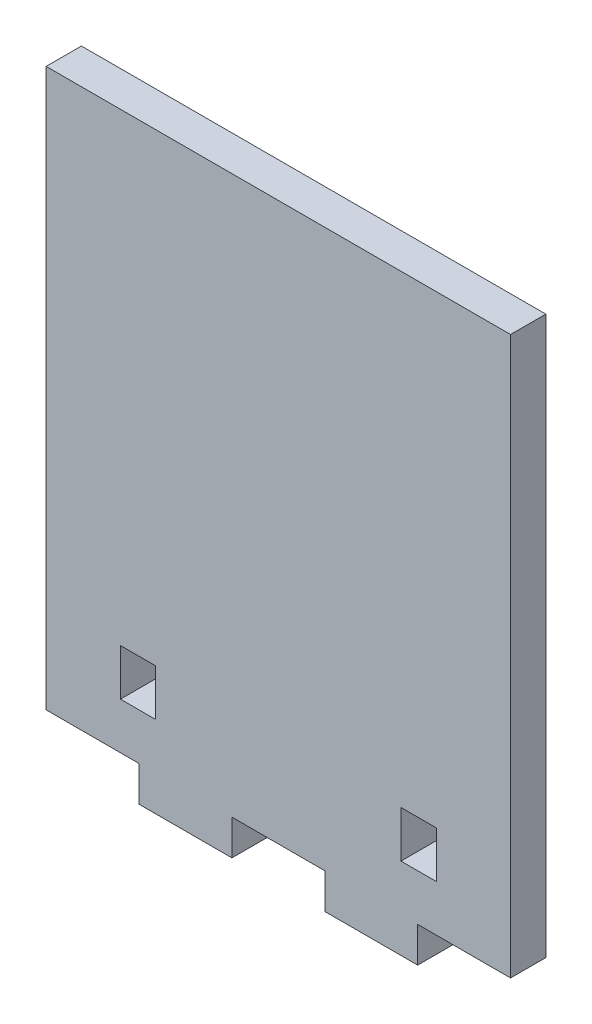
SolidWorks part; units mm, degrees
ref_plane "Front Plane" through (0, 0, 0) normal (0, 0, 1) x (1, 0, 0)
ref_plane "Top Plane" through (0, 0, 0) normal (0, 1, 0) x (1, 0, 0)
ref_plane "Right Plane" through (0, 0, 0) normal (1, 0, 0) x (0, 0, -1)
sketch "Sketch1" plane through (0, 0, 0) normal (0, 0, 1) x (1, 0, 0)
  line L1 (0, 0) -> (63.5, 0)
  line L2 (0, 0) -> (0, 81.026)
  line L3 (0, 81.026) -> (63.5, 81.026)
  line L4 (63.5, 0) -> (63.5, 81.026)
  dimension "D1" = 81.026
  dimension "D2" = 63.5
extrude "Boss-Extrude1" add sketch "Sketch1" along normal blind 4.826
sketch "Sketch2" plane through (0, 0, 4.826) normal (0, 0, 1) x (1, 0, 0)
  line L0 (0, 0) -> (63.5, 0) construction
  line L1 (0, 0) -> (12.7, 0)
  line L2 (0, 0) -> (0, 4.826)
  line L3 (0, 4.826) -> (12.7, 4.826)
  line L4 (12.7, 0) -> (12.7, 4.826)
  line L5 (25.4, 0) -> (38.1, 0)
  line L6 (25.4, 0) -> (25.4, 4.826)
  line L7 (25.4, 4.826) -> (38.1, 4.826)
  line L8 (38.1, 0) -> (38.1, 4.826)
  line L9 (12.7, 4.826) -> (25.4, 4.826) construction
  line L10 (63.5, 0) -> (50.8, 0)
  line L11 (63.5, 0) -> (63.5, 4.826)
  line L12 (63.5, 4.826) -> (50.8, 4.826)
  line L13 (50.8, 0) -> (50.8, 4.826)
  line L14 (38.1, 4.826) -> (50.8, 4.826) construction
  dimension "D1" = 4.826
extrude "Cut-Extrude1" cut sketch "Sketch2" against normal through all
sketch "Sketch3" plane through (0, 0, 0) normal (0, 0, -1) x (-1, 0, 0)
  line L0 (-53.34, 17.526) -> (-53.34, 11.176) construction
  line L1 (-53.34, 17.526) -> (-48.514, 17.526) construction
  line L2 (-48.514, 17.526) -> (-48.514, 11.176) construction
  line L3 (-53.34, 11.176) -> (-48.514, 11.176) construction
  line L4 (-14.986, 17.526) -> (-14.986, 11.176) construction
  line L5 (-14.986, 17.526) -> (-10.16, 17.526) construction
  line L6 (-10.16, 17.526) -> (-10.16, 11.176) construction
  line L7 (-14.986, 11.176) -> (-10.16, 11.176) construction
  line L8 (-53.34, 17.526) -> (-53.34, 11.176)
  line L9 (-53.34, 17.526) -> (-48.514, 17.526)
  line L10 (-48.514, 17.526) -> (-48.514, 11.176)
  line L11 (-53.34, 11.176) -> (-48.514, 11.176)
  line L12 (-50.8, 4.826) -> (-50.8, 0)
  line L13 (-50.8, 0) -> (-38.1, 0)
  line L14 (-38.1, 0) -> (-38.1, 4.826)
  line L15 (-38.1, 4.826) -> (-25.4, 4.826)
  line L16 (-25.4, 4.826) -> (-25.4, 0)
  line L17 (-25.4, 0) -> (-12.7, 0)
  line L18 (-12.7, 0) -> (-12.7, 4.826)
  line L19 (-12.7, 4.826) -> (0, 4.826)
  line L20 (0, 4.826) -> (0, 81.026)
  line L21 (0, 81.026) -> (-63.5, 81.026)
  line L22 (-63.5, 81.026) -> (-63.5, 4.826)
  line L23 (-63.5, 4.826) -> (-50.8, 4.826)
  line L24 (-50.8, 4.826) -> (-50.8, 0)
  line L25 (-50.8, 0) -> (-38.1, 0)
  line L26 (-38.1, 0) -> (-38.1, 4.826)
  line L27 (-38.1, 4.826) -> (-25.4, 4.826)
  line L28 (-25.4, 4.826) -> (-25.4, 0)
  line L29 (-25.4, 0) -> (-12.7, 0)
  line L30 (-12.7, 0) -> (-12.7, 4.826)
  line L31 (-12.7, 4.826) -> (0, 4.826)
  line L32 (0, 4.826) -> (0, 81.026)
  line L33 (0, 81.026) -> (-63.5, 81.026)
  line L34 (-63.5, 81.026) -> (-63.5, 4.826)
  line L35 (-63.5, 4.826) -> (-50.8, 4.826)
  line L36 (-14.986, 17.526) -> (-14.986, 11.176)
  line L37 (-14.986, 17.526) -> (-10.16, 17.526)
  line L38 (-10.16, 17.526) -> (-10.16, 11.176)
  line L39 (-14.986, 11.176) -> (-10.16, 11.176)
  dimension "D1" = 0
extrude "Cut-Extrude2" cut sketch "Sketch3" against normal blind 4.826 contours L8 L11 L10 L9 | L36 L39 L38 L37
equation "\"MDF\"= 0.19in"
equation "\"PVCID\" = 2.067in"
equation "\"PVCOD\" = 2.375in"
equation "\"GenDiameter\"= 60mm"
equation "\"GenCutDiameter\" = 1.8in"
equation "\"GenCutDistance\" = 1"
equation "\"TowerHeight\" = 6in"
equation "\"TowerFrontBase\" = 3in"
equation "\"FunnelHeight\" = 1in"
equation "\"FunnelAngle\" = 20"
equation "\"TowerSideBase\" = 3in"
equation "\"TowerPanelLength\" = 2in"
equation "\"TowerPanelLeeway\" = 0.5in"
equation "\"BaseLength\" = 9in"
equation "\"BaseWidth\" = 10in"
equation "\"WheelHoleLength\" = 3.25in"
equation "\"WheelHoleWidth\" = 26mm"
equation "\"WheelHoleFromBack\" = 1.5in"
equation "\"DropLength\" = 1in"
equation "\"DropWidth\" = 8.5in"
equation "\"BumperWidth\" = 2in"
equation "\"SmallHexDiameter\" = 0.185in"
equation "\"SmallHexHeight\" = 0.701in"
equation "\"ScrewSize\" = 0.106in"
equation "\"BigHexDiameter\" = 0.251in"
equation "\"BigHexHeight\" = 0.374in"
equation "\"PCBThickness\" = 0.066in"
equation "\"ConnectorHeight\" = 0.517in"
equation "\"BoardHeight\" = 0.583in"
equation "\"UnoStackHeight\" = 1.351in"
equation "\"UnoStackWidth\" = 3.053in"
equation "\"UnoStackLength\" = 3.152in"
equation "\"HBridgeWidth\" = 1.797in"
equation "\"HBridgeLength\" = 2.236in"
equation "\"DSWidth\" = 1.820in"
equation "\"DSLength\" = 1.833in"
equation "\"StepperWidth\" = 1.799in"
equation "\"StepperLength\" = 2.248in"
equation "\"ULNWidth\" = 1.304in"
equation "\"ULNLength\" = 1.545in"
equation "\"VSwitchHeight\" = 0.392in"
equation "\"VSwitchWidth\" = 0.637in"
equation "\"VSwitchLength\" = 1.097in"
equation "\"SkateWheelDiameter\" = 80mm"
equation "\"SkateWheelThickness\" = 24mm"
equation "\"BaseDistance\" = 3in"
equation "\"DummyVar\" = 2in"
equation "\"D1@Sketch1\"=\"MDF\"+3in"
equation "\"D1@Boss-Extrude1\"=\"MDF\""
equation "\"D1@Sketch2\"=\"MDF\""
equation "\"D1@Cut-Extrude2\"=\"MDF\""
